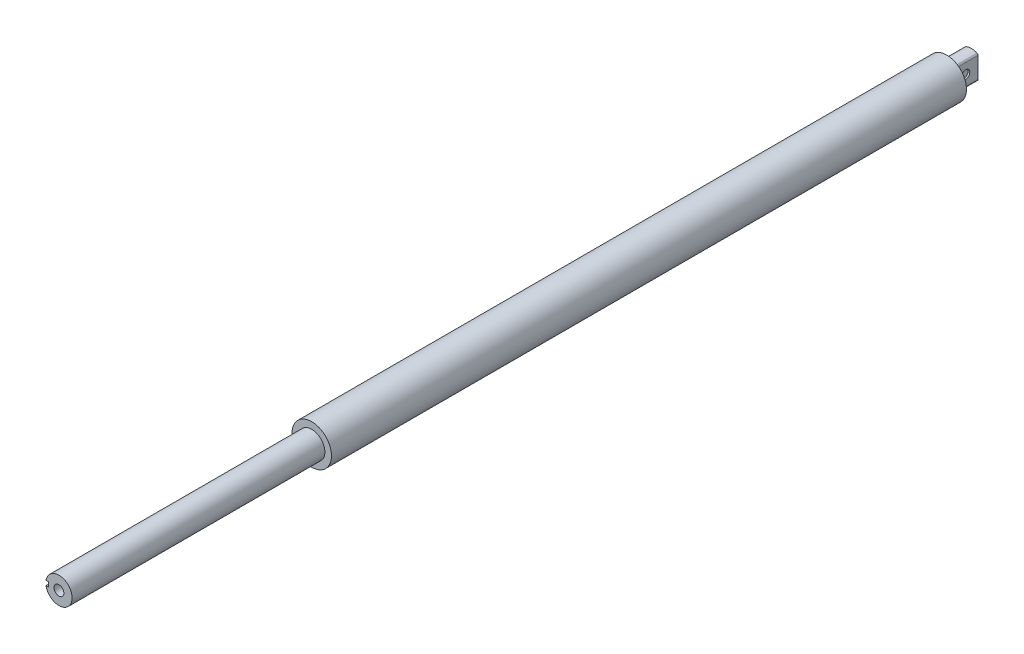
SolidWorks part; units mm, degrees
ref_plane "Front Plane" through (0, 0, 0) normal (0, 0, 1) x (1, 0, 0)
ref_plane "Top Plane" through (0, 0, 0) normal (0, 1, 0) x (1, 0, 0)
ref_plane "Right Plane" through (0, 0, 0) normal (1, 0, 0) x (0, 0, -1)
sketch "Sketch2" plane through (0, 0, 0) normal (0, 1, 0) x (1, 0, 0)
  line L1 (0, -277.5) -> (8, -277.5)
  line L2 (12, -262.5) -> (12, 262.5)
  line L3 (8, 277.5) -> (0, 277.5)
  line L4 (0, -277.5) -> (0, 277.5) construction
  line L7 (8, 262.5) -> (8, 277.5)
  line L8 (12, 262.5) -> (8, 262.5)
  line L9 (-25, 0) -> (12, 0) construction
  line L10 (12, -262.5) -> (8, -262.5)
  line L11 (8, -262.5) -> (8, -277.5)
  line L14 (0, 364.1003) -> (0, -376.0662) construction
  line L15 (0, -277.5) -> (0, 277.5)
  dimension "D2" = 555
  dimension "D5" = 0
  dimension "D1" = 12
  dimension "D4" = 8
  dimension "D3" = 15
  dimension "D6" = 8
  dimension "D7" = 15
revolve "Revolve2" add sketch "Sketch2" angle 360 about L14
sketch "Sketch4" plane through (0, 0, 277.5) normal (0, 0, 1) x (1, 0, 0)
  line L1 (-6.4883, 1.39) -> (-7.8783, 1.39)
  line L2 (-6.4883, 1.39) -> (-6.4883, -1.39)
  line L3 (-6.4883, -1.39) -> (-7.8783, -1.39)
  arc A1 (-7.8783, 1.39) -> (-7.8783, -1.39) centre (0, 0) ccw
  circle A3 centre (0, 0) radius 8 construction
  dimension "D2" = 1.39
  dimension "D1" = 2.78
extrude "Cut-Extrude2" cut sketch "Sketch4" against normal blind 30
sketch "Sketch5" plane through (0, 0, 277.5) normal (0, 0, 1) x (1, 0, 0)
  circle A0 centre (0, 0) radius 3
  arc A1 (-7.8783, -1.39) -> (-7.8783, 1.39) centre (0, 0) ccw construction
  dimension "D1" = 6
extrude "Cut-Extrude3" cut sketch "Sketch5" against normal blind 40
sketch "Sketch6" plane through (0, 0, 262.5) normal (0, 0, 1) x (1, 0, 0)
  circle A0 centre (0, 0) radius 8
  circle A1 centre (0, 0) radius 12
  circle A2 centre (0, 0) radius 12 construction
  arc A3 (-7.8783, -1.39) -> (-7.8783, 1.39) centre (0, 0) ccw construction
extrude "Cut-Extrude4" cut sketch "Sketch6" against normal blind 138.75
sketch "Sketch7" plane through (0, 0, -277.5) normal (0, 0, -1) x (-1, 0, 0)
  line L0 (-4, 6.9282) -> (-4, -6.9282)
  line L1 (4, -6.9282) -> (4, 6.9282)
  line L2 (-4, -6.9282) -> (4, 6.9282) construction
  arc A0 (-4, 6.9282) -> (-4, -6.9282) centre (0, 0) ccw
  circle A1 centre (0, 0) radius 8 construction
  arc A2 (4, -6.9282) -> (4, 6.9282) centre (0, 0) ccw
  dimension "D1" = 8
extrude "Cut-Extrude5" cut sketch "Sketch7" against normal up to surface (15 mm away) up to face at (-8, 0, -262.5)
fillet "Fillet1" radius 1 4 edges at (4, -6.9282, -270) (4, 6.9282, -270) (-4, 6.9282, -270) (-4, -6.9282, -270)
sketch "Sketch8" plane through (4, 0, 0) normal (1, 0, 0) x (0, 0, -1)
  line L0 (277.5, -6.3246) -> (277.5, 6.3246) construction
  line L1 (262.5, -6.3246) -> (277.5, 6.3246) construction
  circle A0 centre (270, 0) radius 2.5
  dimension "D1" = 5
  dimension "D2" = 7.5
extrude "Cut-Extrude6" cut sketch "Sketch8" against normal blind 1
equation "\"shaft inner diameter\"= 15mm "
equation "\"shaft outer diameter\"= 20mm "
equation "\"keyway_height\" = 1.39mm "
equation "\"keyway_width\" = 2.78mm "
equation "\"keyway_length\" = 30mm "
equation "\"steering column length\" = 555mm "
equation "\"u_joint clearance\" = 30mm "
equation "\"u_joint thickness\" = 7.5mm "
equation "\"horizontal shaft length\" = 90mm "
equation "\"pinion width\" = 26.5mm "
equation "\"number of teeth\" = 18mm "
equation "\"D2@Sketch4\"=\"keyway_height\""
equation "\"D1@Sketch4\"=\"keyway_width\""
equation "\"D1@Sketch2\"=\"primary shaft large diameter\"/2"
equation "\"D4@Sketch2\"=\"secondary shaft small diameter\"/2"
equation "\"D1@Cut-Extrude2\"=\"keyway_length\""
equation "\"D2@Sketch2\"=\"steering column length\""
equation "\"steering wheel bolt width\" = 6mm "
equation "\"steering wheel bolt length\" = 40mm "
equation "\"short_bearing_outer_width\" = 10mm "
equation "\"D1@Sketch5\"=\"steering wheel bolt width\""
equation "\"D1@Cut-Extrude3\"=\"steering wheel bolt length\""
equation "\"column bushing diameter\" = \"primary shaft small diameter\" + 4 "
equation "\"column bushing distance\" = \"steering column length\"/4 "
equation "\"D1@Cut-Extrude4\"=\"column bushing distance\""
equation "\"bushing length\" = 40mm "
equation "\"bushing thickness\" = 3mm "
equation "\"column angle\" = 45deg "
equation "\"wheel base\" = 1561mm "
equation "\"track\" = 1354mm "
equation "\"turning radius\" = 2000mm "
equation "\"steering arm length\" = 100mm "
equation "\"turn to lock\" = 0.75mm "
equation "\"pin hole diameter\" = 10mm "
equation "\"rack hole to hole\" = 500mm "
equation "\"rack length\" = \"rack hole to hole\" + \"pin hole diameter\"*2 "
equation "\"rack height\"= \"pin hole diameter\" * 2mm"
equation "\"max turning angle\" = atn(\"wheel base\" / (\"turning radius\" - 0.5 * \"track\")) "
equation "\"max travel\" = 2 * \"steering arm length\" * sin(0.5 * \"max turning angle\") "
equation "\"pitch diameter\" = \"max travel\"/(pi * \"turn to lock\") "
equation "\"module\" = \"pitch diameter\" / \"number of teeth\" "
equation "\"pressure angle\" = 20deg "
equation "\"tie rod length\" = 305mm "
equation "\"tie rod diameter\"= 10mm"
equation "\"primary shaft small diameter\" = 16mm "
equation "\"primary shaft large diameter\" = 24mm "
equation "\"secondary shaft small diameter\" = 16mm "
equation "\"secondary shaft large diameter\" = 25mm "
equation "\"tie rod inner diameter\" = 6.6mm "
equation "\"tie rod outer diameter\" = 8.1mm "
equation "\"D1@Sketch7\"=\"primary shaft small diameter\"/2"
equation "\"D6@Sketch2\"=\"primary shaft small diameter\"/2"
